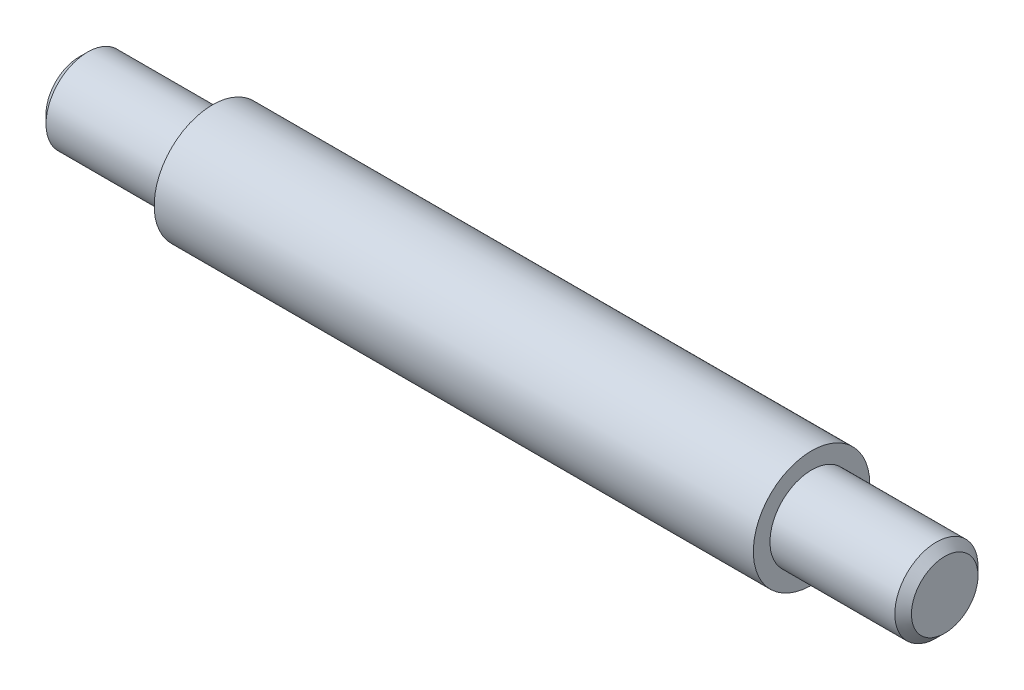
SolidWorks part; units mm, degrees
ref_plane "Piano frontale" through (0, 0, 0) normal (0, 0, 1) x (1, 0, 0)
ref_plane "Piano superiore" through (0, 0, 0) normal (0, 1, 0) x (1, 0, 0)
ref_plane "Piano destro" through (0, 0, 0) normal (1, 0, 0) x (0, 0, -1)
sketch "Schizzo1" plane through (0, 0, 0) normal (1, 0, 0) x (0, 0, -1)
  circle A0 centre (-80, 0) radius 3.5
  dimension "D1" = 7
extrude "Estrusione-Estrusione1" add sketch "Schizzo1" along normal mid plane 36
sketch "Schizzo2" plane through (18, 0, 0) normal (1, 0, 0) x (0, 0, -1)
  circle A0 centre (-80, 0) radius 2.5
  dimension "D1" = 5
extrude "Estrusione-Estrusione2" add sketch "Schizzo2" along normal blind 8
sketch "Schizzo3" plane through (-18, 0, 0) normal (-1, 0, 0) x (0, 0, 1)
  circle A0 centre (80, 0) radius 2.5
  dimension "D1" = 5
extrude "Estrusione-Estrusione3" add sketch "Schizzo3" along normal blind 8
chamfer "Smusso1" distance 0.5 angle 45 2 edges at (-26, 0, 82.5) (26, 0, 77.5)
